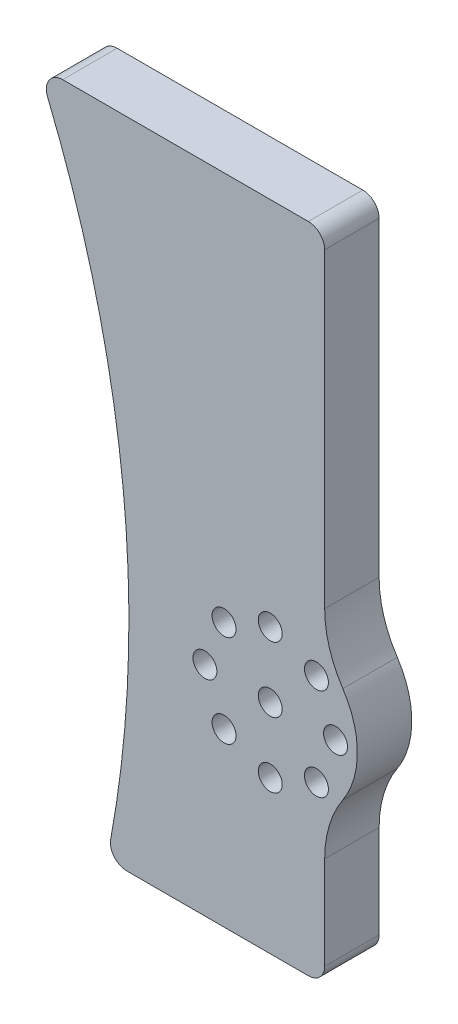
SolidWorks part; units mm, degrees
material "ABS"
ref_plane "正面" through (0, 0, 0) normal (0, 0, 1) x (1, 0, 0)
ref_plane "平面" through (0, 0, 0) normal (0, 1, 0) x (1, 0, 0)
ref_plane "右側面" through (0, 0, 0) normal (1, 0, 0) x (0, 0, -1)
sketch "ｽｹｯﾁ1" plane through (0, 0, 0) normal (0, 0, 1) x (1, 0, 0)
  line L0 (0, 0) -> (0, 60) construction
  line L1 (-5, 60) -> (5, 60)
  line L2 (-5, 60) -> (-5, 29.9499)
  line L3 (-5, 0) -> (5, 0)
  line L4 (5, 60) -> (5, 29.9499)
  line L5 (-5, 10.0501) -> (-5, 0)
  line L6 (5, 10.0501) -> (5, 0)
  circle A0 centre (0, 20) radius 1.1
  circle A1 centre (0, 20) radius 6 construction
  circle A2 centre (0, 14) radius 1.1
  circle A3 centre (-4.2426, 15.7574) radius 1.1
  circle A4 centre (-6, 20) radius 1.1
  circle A5 centre (-4.2426, 24.2426) radius 1.1
  circle A6 centre (0, 26) radius 1.1
  circle A7 centre (4.2426, 24.2426) radius 1.1
  circle A8 centre (6, 20) radius 1.1
  circle A9 centre (4.2426, 15.7574) radius 1.1
  arc A10 (-6.6667, 24.4222) -> (-6.6667, 15.5778) centre (0, 20) ccw
  arc A11 (6.6667, 15.5778) -> (6.6667, 24.4222) centre (0, 20) ccw
  arc A12 (-6.6667, 24.4222) -> (-5, 29.9499) centre (-15, 29.9499) ccw
  arc A13 (-6.6667, 15.5778) -> (-5, 10.0501) centre (-15, 10.0501) cw
  arc A14 (5, 10.0501) -> (6.6667, 15.5778) centre (15, 10.0501) cw
  arc A15 (5, 29.9499) -> (6.6667, 24.4222) centre (15, 29.9499) ccw
  point P29 (0, 20)
  point P35 (-5, 13.755)
  point P38 (5, 13.755)
  dimension "D3" = 2.2
  dimension "D5" = 12
  dimension "D6" = 2.2
  dimension "D8" = 16
  dimension "D9" = 10
  dimension "D1" = 10
  dimension "D2" = 60
  dimension "D4" = 20
  dimension "D7" = 8
extrude "ﾎﾞｽ - 押し出し1" add sketch "ｽｹｯﾁ1" along normal blind 5
sketch "ｽｹｯﾁ2" plane through (0, 0, 0) normal (0, 0, -1) x (-1, 0, 0)
  line L0 (5, 10.0501) -> (5, 0) construction
  line L1 (5, 60) -> (5, 29.9499) construction
  line L2 (5, 10.0501) -> (5, 0)
  line L3 (5, 60) -> (5, 29.9499)
  line L4 (5, 60) -> (21.3281, 60)
  line L5 (5, 0) -> (15, 0)
  arc A0 (6.6667, 15.5778) -> (5, 10.0501) centre (15, 10.0501) ccw construction
  arc A1 (6.6667, 15.5778) -> (6.6667, 24.4222) centre (0, 20) ccw construction
  arc A2 (5, 29.9499) -> (6.6667, 24.4222) centre (15, 29.9499) ccw construction
  arc A3 (6.6667, 15.5778) -> (5, 10.0501) centre (15, 10.0501) ccw
  arc A4 (6.6667, 15.5778) -> (6.6667, 24.4222) centre (0, 20) ccw
  arc A5 (5, 29.9499) -> (6.6667, 24.4222) centre (15, 29.9499) ccw
  arc A6 (21.3281, 60) -> (15, 0) centre (112.9796, 20) ccw
  point P14 (0, 0)
  dimension "D1" = 200
  dimension "D2" = 10
extrude "ﾎﾞｽ - 押し出し2" add sketch "ｽｹｯﾁ2" against normal blind 5
fillet "ﾌｨﾚｯﾄ1" radius 1.5 4 edges at (5, 0, 2.5) (-15, 0, 2.5) (-21.3281, 60, 2.5) (5, 60, 2.5)
